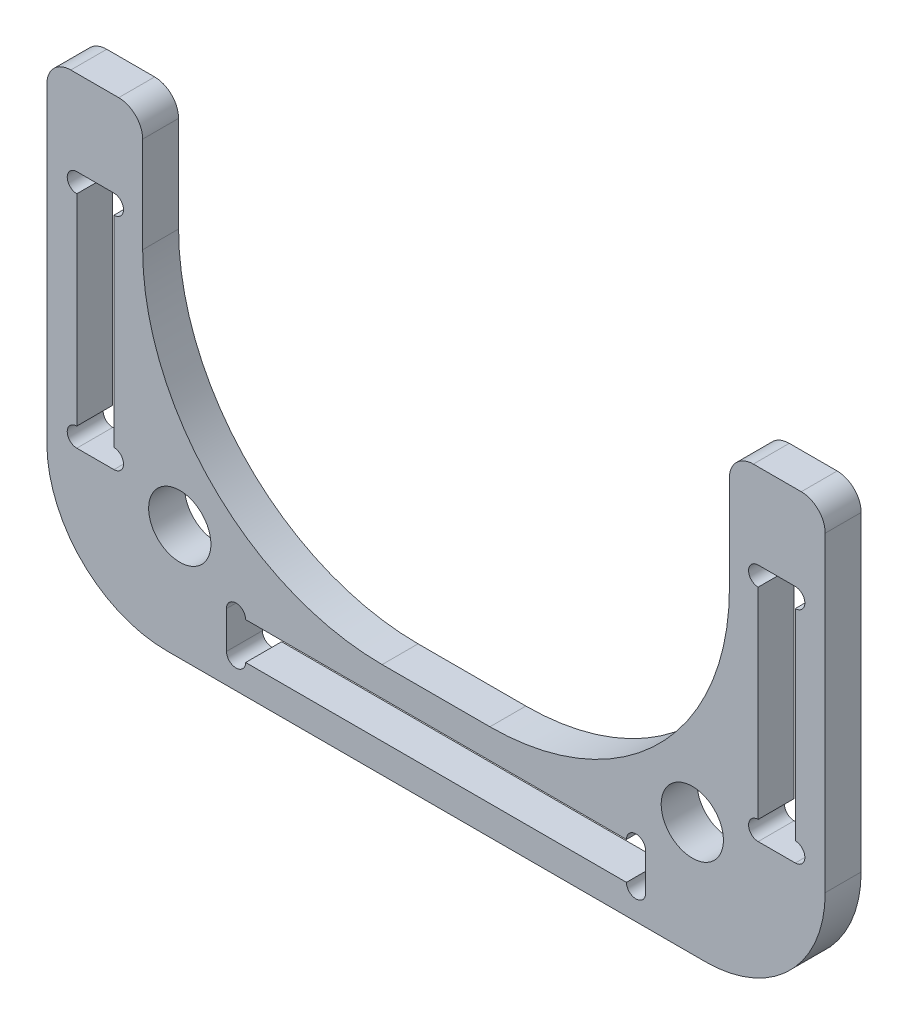
SolidWorks part; units mm, degrees
material "Thornel Mat VMA"
ref_plane "Front Plane" through (0, 0, 0) normal (0, 0, 1) x (1, 0, 0)
ref_plane "Top Plane" through (0, 0, 0) normal (0, 1, 0) x (1, 0, 0)
ref_plane "Right Plane" through (0, 0, 0) normal (1, 0, 0) x (0, 0, -1)
sketch "Sketch1" plane through (0, 0, 0) normal (0, 0, 1) x (1, 0, 0)
  line L0 (0, 0) -> (0, 8) construction
  line L1 (0, 0) -> (-32.5, 0)
  line L2 (-32.5, 0) -> (-32.5, 38)
  line L3 (0, 8) -> (-24.5, 8)
  line L4 (-24.5, 8) -> (-24.5, 38)
  line L5 (0, 0) -> (0, 8) construction
  line L6 (-32.5, 38) -> (-24.5, 38)
  line L7 (0, 0) -> (32.5, 0)
  line L8 (0, 8) -> (24.5, 8)
  line L9 (32.5, 38) -> (24.5, 38)
  line L10 (24.5, 8) -> (24.5, 38)
  line L11 (32.5, 0) -> (32.5, 38)
  point P3 (0, 11.1934)
  dimension "D1" = 65
  dimension "D3" = 30
  dimension "D2" = 8
extrude "Boss-Extrude1" add sketch "Sketch1" along normal blind 3
fillet "Fillet1" radius 20 2 edges at (24.5, 8, 1.5) (-24.5, 8, 1.5)
sketch "Sketch2" plane through (0, 0, 3) normal (0, 0, 1) x (1, 0, 0)
  line L0 (-28.45, 38) -> (-28.45, 0) construction
  line L1 (-24.5, 38) -> (-32.5, 38) construction
  line L2 (-32.5, 0) -> (32.5, 0) construction
  line L3 (-32.5, 38) -> (-32.5, 0) construction
  line L4 (-30, 10.9) -> (-26.9, 10.9)
  line L5 (-30, 12.5) -> (-30, 29.3)
  line L6 (-30, 30.9) -> (-26.9, 30.9)
  line L7 (-26.9, 12.5) -> (-26.9, 29.3)
  line L8 (-30, 10.9) -> (-26.9, 30.9) construction
  line L9 (-30, 30.9) -> (-26.9, 10.9) construction
  line L10 (0, 0) -> (0, 8) construction
  line L11 (4.5, 8) -> (-4.5, 8) construction
  line L12 (30, 30.9) -> (26.9, 10.9) construction
  line L13 (30, 10.9) -> (26.9, 30.9) construction
  line L14 (28.45, 38) -> (28.45, 0) construction
  line L15 (26.9, 12.5) -> (26.9, 29.3)
  line L16 (30, 30.9) -> (26.9, 30.9)
  line L17 (30, 12.5) -> (30, 29.3)
  line L18 (30, 10.9) -> (26.9, 10.9)
  line L20 (-15.9, 2.45) -> (15.9, 2.45)
  line L21 (-17.5, 2.45) -> (-17.5, 5.55)
  line L22 (-15.9, 5.55) -> (15.9, 5.55)
  line L23 (17.5, 2.45) -> (17.5, 5.55)
  line L24 (-17.5, 2.45) -> (17.5, 5.55) construction
  line L25 (-17.5, 5.55) -> (17.5, 2.45) construction
  arc A0 (-30, 30.9) -> (-30, 29.3) centre (-30, 30.1) ccw
  arc A1 (-26.9, 29.3) -> (-26.9, 30.9) centre (-26.9, 30.1) ccw
  arc A2 (-30, 12.5) -> (-30, 10.9) centre (-30, 11.7) ccw
  arc A3 (-26.9, 10.9) -> (-26.9, 12.5) centre (-26.9, 11.7) ccw
  arc A4 (26.9, 10.9) -> (26.9, 12.5) centre (26.9, 11.7) cw
  arc A5 (30, 12.5) -> (30, 10.9) centre (30, 11.7) cw
  arc A6 (26.9, 29.3) -> (26.9, 30.9) centre (26.9, 30.1) cw
  arc A7 (30, 30.9) -> (30, 29.3) centre (30, 30.1) cw
  arc A8 (-15.9, 5.55) -> (-17.5, 5.55) centre (-16.7, 5.55) ccw
  arc A9 (-17.5, 2.45) -> (-15.9, 2.45) centre (-16.7, 2.45) ccw
  arc A10 (17.5, 5.55) -> (15.9, 5.55) centre (16.7, 5.55) ccw
  arc A11 (15.9, 2.45) -> (17.5, 2.45) centre (16.7, 2.45) ccw
  point P6 (-28.45, 20.9)
  point P40 (28.45, 20.9)
  point P41 (0, 4)
  point P51 (0, 0)
  dimension "D4" = 1.6
  dimension "D7" = 1.6
  dimension "D1" = 20
  dimension "D2" = 2.5
  dimension "D3" = 3.1
  dimension "D5" = 3.1
  dimension "D6" = 35
  dimension "D8" = 7.1
extrude "Cut-Extrude1" cut sketch "Sketch2" against normal through all
sketch "Sketch3" plane through (0, 0, 3) normal (0, 0, 1) x (1, 0, 0)
  line L0 (-26.9, 12.5) -> (-26.9, 29.3) construction
  line L1 (15.9, 5.55) -> (-15.9, 5.55) construction
  line L2 (0, 0) -> (0, 8) construction
  line L3 (4.5, 8) -> (-4.5, 8) construction
  circle A1 centre (-21.4, 9.55) radius 2.6
  circle A2 centre (21.4, 9.55) radius 2.6
  dimension "D1" = 5.2
  dimension "D2" = 5.5
  dimension "D3" = 4
extrude "Cut-Extrude2" cut sketch "Sketch3" against normal through all
fillet "Fillet2" radius 10 2 edges at (-32.5, 0, 1.5) (32.5, 0, 1.5)
fillet "Fillet3" radius 2 4 edges at (-32.5, 38, 1.5) (-24.5, 38, 1.5) (24.5, 38, 1.5) (32.5, 38, 1.5)
